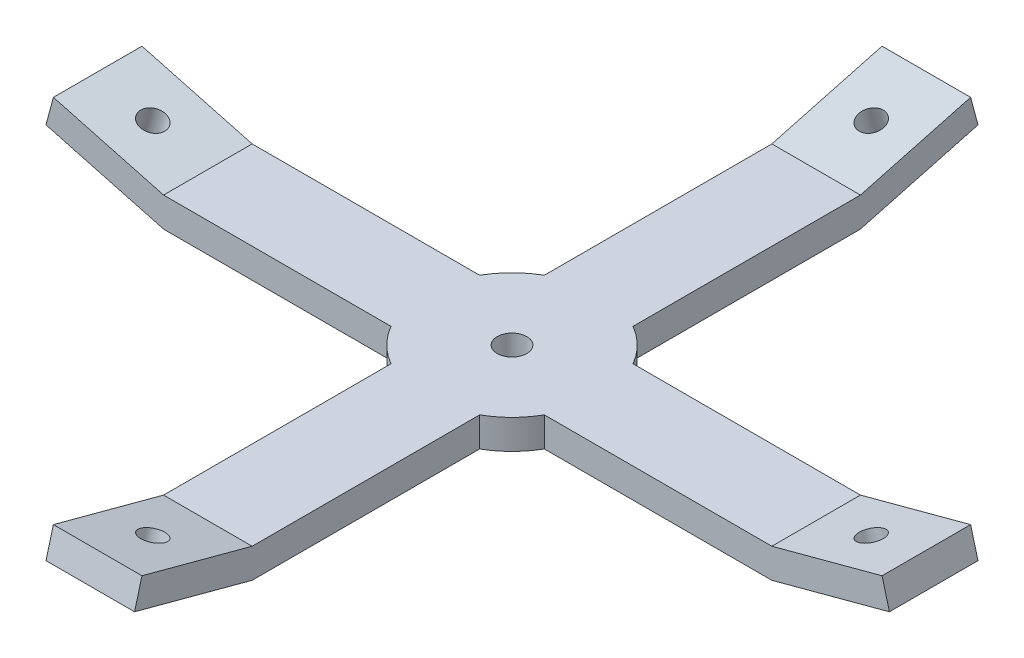
SolidWorks part; units mm, degrees
ref_plane "Спереди" through (0, 0, 0) normal (0, 0, 1) x (1, 0, 0)
ref_plane "Сверху" through (0, 0, 0) normal (0, 1, 0) x (1, 0, 0)
ref_plane "Справа" through (0, 0, 0) normal (1, 0, 0) x (0, 0, -1)
sketch "Эскиз1" plane through (0, 0, 0) normal (0, 1, 0) x (1, 0, 0)
  line L0 (0, 0) -> (0, 51.5) construction
  line L1 (0, 0) -> (-51.5, 0) construction
  line L2 (0, 0) -> (51.5, 0) construction
  line L3 (-7.5, 51.5) -> (7.5, 51.5)
  line L4 (-7.5, 51.5) -> (-7.5, 12.9904)
  line L5 (7.5, 51.5) -> (7.5, 12.9904)
  line L7 (-51.5, 7.5) -> (-51.5, -7.5)
  line L8 (-51.5, 7.5) -> (-12.9904, 7.5)
  line L9 (-51.5, -7.5) -> (-12.9904, -7.5)
  line L11 (51.5, 7.5) -> (51.5, -7.5)
  line L12 (51.5, 7.5) -> (12.9904, 7.5)
  line L13 (51.5, -7.5) -> (12.9904, -7.5)
  line L16 (-7.5, -12.9904) -> (-7.5, -51.5)
  line L17 (7.5, -12.9904) -> (7.5, -51.5)
  line L18 (-7.5, -51.5) -> (7.5, -51.5)
  line L19 (0, 0) -> (0, -51.5) construction
  arc A0 (7.5, -12.9904) -> (12.9904, -7.5) centre (0, 0) ccw
  arc A1 (12.9904, 7.5) -> (7.5, 12.9904) centre (0, 0) ccw
  arc A2 (-7.5, 12.9904) -> (-12.9904, 7.5) centre (0, 0) ccw
  arc A3 (-12.9904, -7.5) -> (-7.5, -12.9904) centre (0, 0) ccw
  point P4 (0, 51.5)
  point P20 (-51.5, 0)
  point P22 (51.5, 0)
  dimension "D1" = 30
  dimension "D2" = 51.5
  dimension "D3" = 15
  dimension "D4" = 90
  dimension "D5" = 90
  dimension "D6" = 15
  dimension "D7" = 15
  dimension "D8" = 15
extrude "Бобышка-Вытянуть1" add sketch "Эскиз1" along normal blind 5
sketch "Эскиз2" plane through (7.5, 0, 0) normal (1, 0, 0) x (0, 0, -1)
  line L0 (-51.5, 0) -> (-71.4103, 5.3349)
  line L2 (-70.1603, 10) -> (-51.5, 5)
  line L3 (-51.5, 5) -> (-51.5, 0) construction
  line L4 (-51.5, 0) -> (-12.9904, 0) construction
  line L5 (-51.5, 5) -> (-12.9904, 5) construction
  line L6 (-51.5, 5) -> (-51.5, 0)
  line L7 (-70.1603, 10) -> (-71.4103, 5.3349)
  dimension "D1" = 15
  dimension "D2" = 5
sketch "Эскиз3" plane through (0, 0, -7.5) normal (0, 0, -1) x (-1, 0, 0)
  line L0 (-51.5, 0) -> (-71.4103, 5.3349)
  line L2 (-70.1603, 10) -> (-51.5, 5)
  line L3 (-51.5, 0) -> (-12.9904, 0) construction
  line L5 (-51.5, 5) -> (-51.5, 0)
  line L6 (-70.1603, 10) -> (-71.4103, 5.3349)
  line L7 (-51.5, 5) -> (-12.9904, 5) construction
  dimension "D1" = 15
  dimension "D2" = 5
sketch "Эскиз4" plane through (-7.5, 0, 0) normal (-1, 0, 0) x (0, 0, 1)
  line L0 (-51.5, 0) -> (-71.4103, 5.3349)
  line L2 (-70.1603, 10) -> (-51.5, 5)
  line L3 (-51.5, 0) -> (-12.9904, 0) construction
  line L5 (-51.5, 5) -> (-51.5, 0)
  line L6 (-70.1603, 10) -> (-71.4103, 5.3349)
  line L7 (-51.5, 5) -> (-12.9904, 5) construction
  dimension "D1" = 15
  dimension "D2" = 5
sketch "Эскиз5" plane through (0, 0, 7.5) normal (0, 0, 1) x (1, 0, 0)
  line L0 (-51.5, 0) -> (-71.4103, 5.3349)
  line L2 (-70.1603, 10) -> (-51.5, 5)
  line L3 (-51.5, 5) -> (-51.5, 0)
  line L4 (-51.5, 0) -> (-12.9904, 0) construction
  line L6 (-70.1603, 10) -> (-71.4103, 5.3349)
  line L7 (-51.5, 5) -> (-12.9904, 5) construction
  dimension "D1" = 15
  dimension "D2" = 5
extrude "Бобышка-Вытянуть6" add sketch "Эскиз2" against normal blind 15
extrude "Бобышка-Вытянуть7" add sketch "Эскиз3" against normal blind 15
extrude "Бобышка-Вытянуть8" add sketch "Эскиз4" against normal blind 15
extrude "Бобышка-Вытянуть9" add sketch "Эскиз5" against normal blind 15
hole_wizard "Отверстие обработанное метчиком M61" positions "Эскиз6" profile "Эскиз7" tap size "M6" standard "ISO" end condition through all
sketch "Эскиз6" plane through (0, 5, 0) normal (0, 1, 0) x (1, 0, 0)
  point P0 (0, 0)
sketch "Эскиз7" plane through (0, 5, 0) normal (1, 0, 0) x (0, 0, 1)
  line L0 (0, 0) -> (0, 5)
  line L1 (0, 5) -> (2.5, 5)
  line L2 (2.5, 5) -> (2.5, 0)
  line L5 (2.5, 0) -> (0, 0)
  line L11 (0, -6.35) -> (0, 107.95) construction
  dimension "Диаметр проходного сверла" = 5
  dimension "Глубина проходного сверла" = 5
cosmetic thread "Отверстие резьбы1" parameters "D2"=6
sketch "Эскиз8" plane through (0, 0, 0) normal (0, 1, 0) x (1, 0, 0)
  line L0 (-70.1603, 0) -> (70.1603, 0) construction
  line L1 (-70.1603, 7.5) -> (-70.1603, -7.5) construction
  line L3 (0, 70.1603) -> (0, -70.1603) construction
  line L6 (70.1603, -7.5) -> (70.1603, 7.5) construction
  line L7 (7.5, 70.1603) -> (-7.5, 70.1603) construction
  line L8 (-7.5, -70.1603) -> (7.5, -70.1603) construction
  line L9 (-60.8301, 7.5) -> (-60.8301, -7.5) construction
  line L10 (-51.5, 7.5) -> (-70.1603, 7.5) construction
  line L11 (-51.5, -7.5) -> (-70.1603, -7.5) construction
  line L12 (-7.5, 60.8301) -> (7.5, 60.8301) construction
  line L13 (-7.5, 51.5) -> (-7.5, 70.1603) construction
  line L14 (7.5, 51.5) -> (7.5, 70.1603) construction
  line L15 (60.8301, 7.5) -> (60.8301, -7.5) construction
  line L16 (51.5, 7.5) -> (70.1603, 7.5) construction
  line L17 (51.5, -7.5) -> (70.1603, -7.5) construction
  line L18 (-7.5, -60.8301) -> (7.5, -60.8301) construction
  line L19 (-7.5, -51.5) -> (-7.5, -70.1603) construction
  line L20 (7.5, -51.5) -> (7.5, -70.1603) construction
  point P13 (-70.1603, 0)
  point P16 (70.1603, 0)
  point P19 (0, 70.1603)
  point P22 (0, -70.1603)
hole_wizard "Отверстие обработанное метчиком M51" positions "Трехмерный эскиз1" profile "Эскиз9" tap size "M5" standard "ISO" end condition through all
sketch3d "Трехмерный эскиз1"
  line L0 (0, 0, 60.8301) -> (0, 7.5, 60.8301) construction
  line L1 (-7.5, 0, 60.8301) -> (7.5, 0, 60.8301) construction
  line L3 (60.8301, 0, 0) -> (60.8301, 7.5, 0) construction
  line L4 (60.8301, 0, -7.5) -> (60.8301, 0, 7.5) construction
  line L6 (0, 0, -60.8301) -> (0, 7.5, -60.8301) construction
  line L7 (-7.5, 0, -60.8301) -> (7.5, 0, -60.8301) construction
  line L9 (-60.8301, 0, 0) -> (-60.8301, 7.5, 0) construction
  line L10 (-60.8301, 0, -7.5) -> (-60.8301, 0, 7.5) construction
  point P1 (0, 7.5, 60.8301)
  point P6 (60.8301, 7.5, 0)
  point P11 (0, 7.5, -60.8301)
  point P16 (-60.8301, 7.5, 0)
sketch "Эскиз9" plane through (-60.8301, 7.5, 0) normal (0, 0, 1) x (-0.9659, 0.2588, 0)
  line L0 (0, 0) -> (0, 9.9828)
  line L1 (0, 9.9828) -> (2.1, 9.9828)
  line L2 (2.1, 9.9828) -> (2.1, 0)
  line L5 (2.1, 0) -> (0, 0)
  line L11 (0, -6.35) -> (0, 107.95) construction
  dimension "Диаметр проходного сверла" = 4.2
  dimension "Глубина проходного сверла" = 9.9828
cosmetic thread "Отверстие резьбы2" parameters "D2"=5
cosmetic thread "Отверстие резьбы3" parameters "D2"=5
cosmetic thread "Отверстие резьбы4" parameters "D2"=5
cosmetic thread "Отверстие резьбы5" parameters "D2"=5
